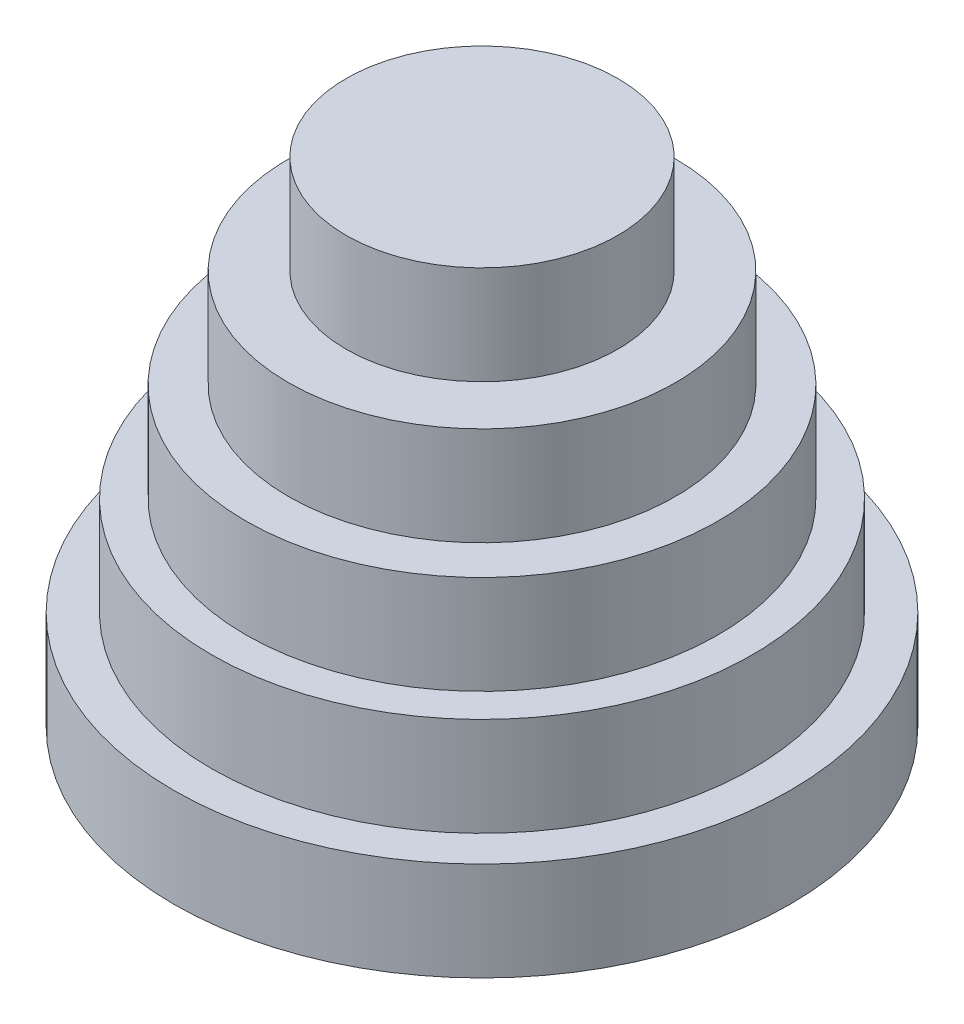
SolidWorks part; units mm, degrees
material "AISI 1020"
ref_plane "Plan de face" through (0, 0, 0) normal (0, 0, 1) x (1, 0, 0)
ref_plane "Plan de dessus" through (0, 0, 0) normal (0, 1, 0) x (1, 0, 0)
ref_plane "Plan de droite" through (0, 0, 0) normal (1, 0, 0) x (0, 0, -1)
sketch "Sketch2" plane through (0, 0, 0) normal (0, 0, 1) x (1, 0, 0)
  line L1 (55, 0) -> (-55, 0) construction
  line L2 (0, -55) -> (0, 55) construction
  line L3 (0, 40) -> (0, 0)
  line L4 (0, 0) -> (-25, 0)
  line L5 (-25, 0) -> (-25, 8)
  line L6 (-25, 8) -> (-21.9422, 8)
  line L7 (-21.9422, 8) -> (-21.9422, 16)
  line L8 (-21.9422, 16) -> (-19.1542, 16)
  line L9 (-19.1542, 16) -> (-19.1542, 24)
  line L10 (-19.1542, 24) -> (-15.7078, 24)
  line L11 (-15.7078, 24) -> (-15.7078, 32)
  line L12 (-15.7078, 32) -> (-11.0244, 32)
  line L13 (-11.0244, 32) -> (-11.0244, 40)
  line L14 (-11.0244, 40) -> (0, 40)
  point P6 (0, 0)
  point P18 (0, 0)
  point P19 (0, 0)
  point P20 (-11.0244, 40)
  point P21 (-16.1717, 31.8968)
  point P22 (-15.7078, 32)
  point P23 (-19.1542, 24)
other "AlignGroup1" parameters "D1"=22.9002, "D2"=31.5154
revolve "Revolve1" add sketch "Sketch2" angle 360 about L3
